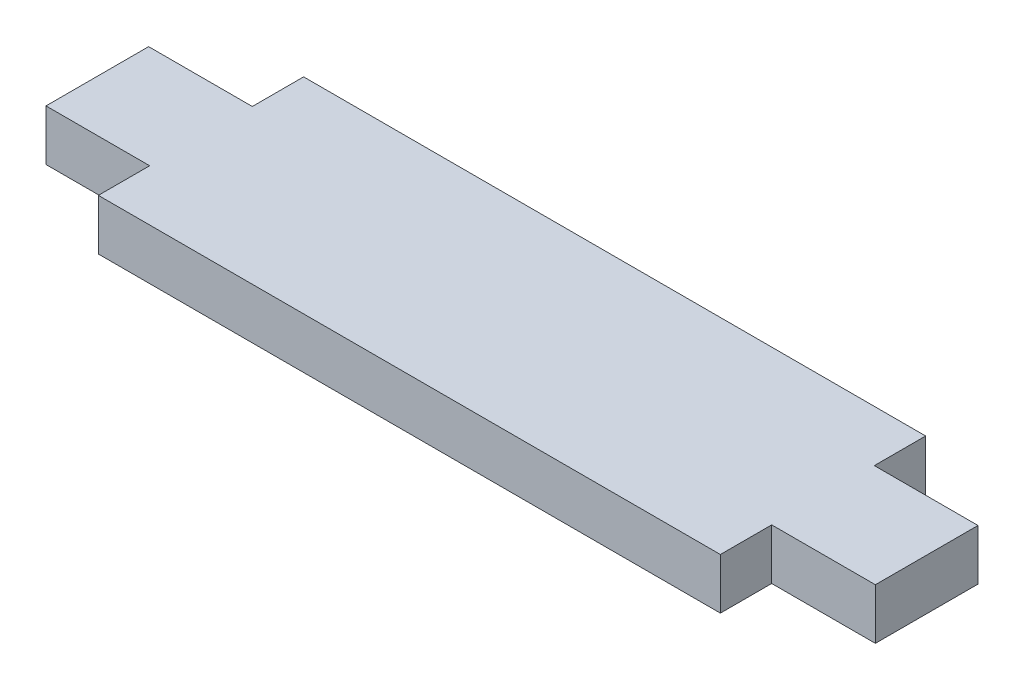
SolidWorks part; units mm, degrees
ref_plane "Front Plane" through (0, 0, 0) normal (0, 0, 1) x (1, 0, 0)
ref_plane "Top Plane" through (0, 0, 0) normal (0, 1, 0) x (1, 0, 0)
ref_plane "Right Plane" through (0, 0, 0) normal (1, 0, 0) x (0, 0, -1)
sketch "Sketch1" plane through (0, 0, 0) normal (1, 0, 0) x (0, 0, -1)
  line L1 (-9.9, -2.45) -> (9.9, -2.45)
  line L2 (-9.9, -2.45) -> (-9.9, 2.45)
  line L3 (-9.9, 2.45) -> (9.9, 2.45)
  line L4 (9.9, -2.45) -> (9.9, 2.45)
  line L5 (-9.9, -2.45) -> (9.9, 2.45) construction
  line L6 (-9.9, 2.45) -> (9.9, -2.45) construction
  point P0 (0, 0)
  dimension "D1" = 4.9
  dimension "D2" = 19.8
extrude "Boss-Extrude1" add sketch "Sketch1" along normal mid plane 60
sketch "Sketch2" plane through (30, 0, 0) normal (1, 0, 0) x (0, 0, -1)
  line L0 (9.9, 2.45) -> (-9.9, 2.45) construction
  line L1 (-4.95, -2.45) -> (4.95, -2.45)
  line L2 (-4.95, -2.45) -> (-4.95, 2.45)
  line L3 (-4.95, 2.45) -> (4.95, 2.45)
  line L4 (4.95, -2.45) -> (4.95, 2.45)
  line L5 (-4.95, -2.45) -> (4.95, 2.45) construction
  line L6 (-4.95, 2.45) -> (4.95, -2.45) construction
  point P0 (0, 0)
  dimension "D1" = 9.9
extrude "Boss-Extrude2" add sketch "Sketch2" along normal blind 10
mirror "Mirror1" about plane through (0, 0, 0) normal (1, 0, 0) of "Boss-Extrude2"
